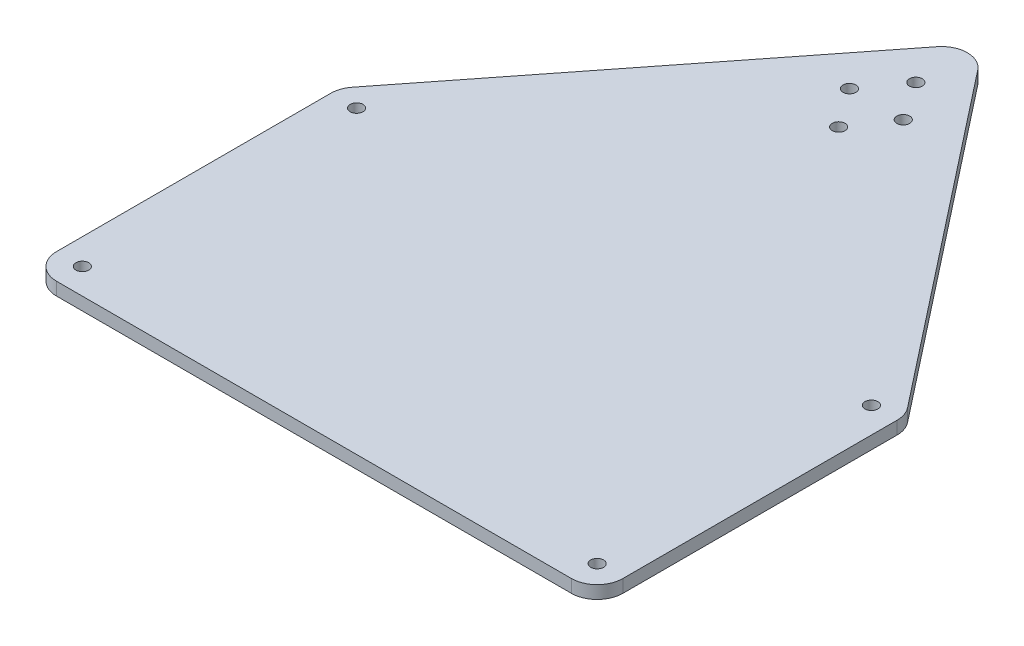
SolidWorks part; units mm, degrees
ref_plane "Front Plane" through (0, 0, 0) normal (0, 0, 1) x (1, 0, 0)
ref_plane "Top Plane" through (0, 0, 0) normal (0, 1, 0) x (1, 0, 0)
ref_plane "Right Plane" through (0, 0, 0) normal (1, 0, 0) x (0, 0, -1)
sketch "Sketch1" plane through (0, 0, 0) normal (0, 1, 0) x (1, 0, 0)
  line L0 (-125.5793, 0) -> (128.4207, 0)
  line L1 (141.1207, 12.7) -> (141.1207, 148.0075)
  line L2 (138.4069, 155.8539) -> (11.4069, 317.4902)
  line L3 (-8.5656, 317.4902) -> (-135.5656, 155.8539)
  line L4 (-138.2793, 148.0075) -> (-138.2793, 12.7)
  arc A0 (-125.5793, 0) -> (-138.2793, 12.7) centre (-125.5793, 12.7) cw
  arc A1 (128.4207, 0) -> (141.1207, 12.7) centre (128.4207, 12.7) ccw
  arc A2 (141.1207, 148.0075) -> (138.4069, 155.8539) centre (128.4207, 148.0075) ccw
  arc A3 (11.4069, 317.4902) -> (-8.5656, 317.4902) centre (1.4207, 309.6439) ccw
  arc A4 (-135.5656, 155.8539) -> (-138.2793, 148.0075) centre (-125.5793, 148.0075) ccw
  circle A5 centre (1.4207, 296.9439) radius 3.175
  circle A6 centre (-12.2951, 277.8939) radius 3.175
  circle A7 centre (14.2584, 277.8939) radius 3.175
  circle A8 centre (1.4207, 258.8439) radius 3.175
  circle A9 centre (-125.5793, 148.0075) radius 3.175
  circle A10 centre (128.4207, 148.0075) radius 3.175
  circle A11 centre (128.4207, 12.7) radius 3.175
  circle A12 centre (-125.5793, 12.7) radius 3.175
  point P8 (-138.2793, 0)
  point P11 (141.1207, 0)
  point P14 (141.1207, 152.4)
  point P17 (1.4207, 330.2)
  point P32 (1.4207, 322.3439)
  point P33 (0, 0)
  point P34 (0, 0)
  point P35 (0, 0)
  point P36 (0, 0)
  dimension "D5" = 12.7
  dimension "D6" = 6.35
  dimension "D7" = 6.35
  dimension "D8" = 6.35
  dimension "D9" = 6.35
  dimension "D10" = 6.35
  dimension "D11" = 6.35
  dimension "D12" = 6.35
  dimension "D13" = 6.35
  dimension "D1" = 279.4
  dimension "D2" = 152.4
  dimension "D3" = 330.2
  dimension "D4" = 1.4207
  dimension "D14" = 25.4
  dimension "D15" = 31.75
  dimension "D16" = 63.5
  dimension "D17" = 14.2584
  dimension "D18" = 12.2951
extrude "Boss-Extrude2" add sketch "Sketch1" along normal blind 6.35
sketch "Sketch3" plane through (0, 0, 0) normal (0, 1, 0) x (1, 0, 0)
  circle A0 centre (128.4207, 12.7) radius 3.175 construction
  circle A1 centre (-125.5793, 12.7) radius 3.175 construction
  circle A2 centre (128.4207, 148.0075) radius 3.175 construction
  circle A3 centre (-125.5793, 148.0075) radius 3.175 construction
  circle A4 centre (1.4207, 258.8439) radius 3.175 construction
  circle A5 centre (14.2584, 277.8939) radius 3.175 construction
  circle A6 centre (-12.2951, 277.8939) radius 3.175 construction
  circle A7 centre (1.4207, 296.9439) radius 3.175 construction
  circle A8 centre (128.4207, 12.7) radius 3.175
  circle A9 centre (-125.5793, 12.7) radius 3.175
  circle A10 centre (128.4207, 148.0075) radius 3.175
  circle A11 centre (-125.5793, 148.0075) radius 3.175
  circle A12 centre (1.4207, 258.8439) radius 3.175
  circle A13 centre (14.2584, 277.8939) radius 3.175
  circle A14 centre (-12.2951, 277.8939) radius 3.175
  circle A15 centre (1.4207, 296.9439) radius 3.175
